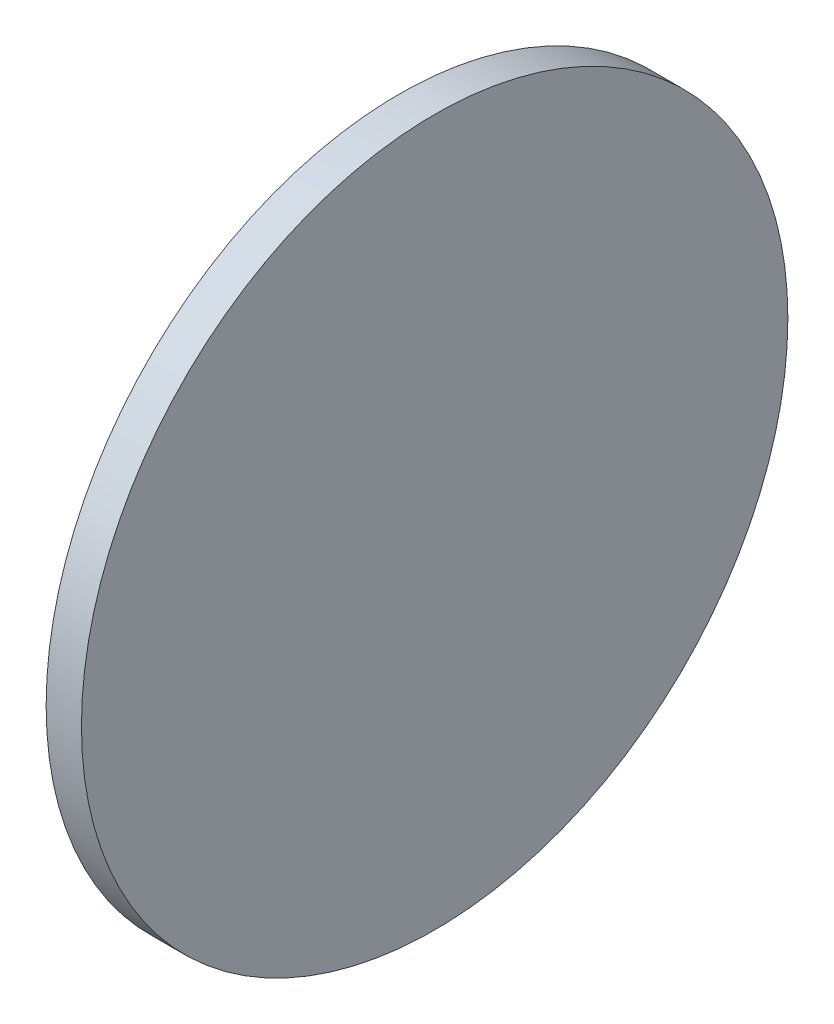
SolidWorks part; units mm, degrees
ref_plane "Front Plane" through (0, 0, 0) normal (0, 0, 1) x (1, 0, 0)
ref_plane "Top Plane" through (0, 0, 0) normal (0, 1, 0) x (1, 0, 0)
ref_plane "Right Plane" through (0, 0, 0) normal (1, 0, 0) x (0, 0, -1)
sketch "Sketch1" plane through (0, 0, 0) normal (1, 0, 0) x (0, 0, -1)
  circle A0 centre (0, 0) radius 25.4
  dimension "D1" = 50.8
extrude "Boss-Extrude1" add sketch "Sketch1" along normal blind 2.54
